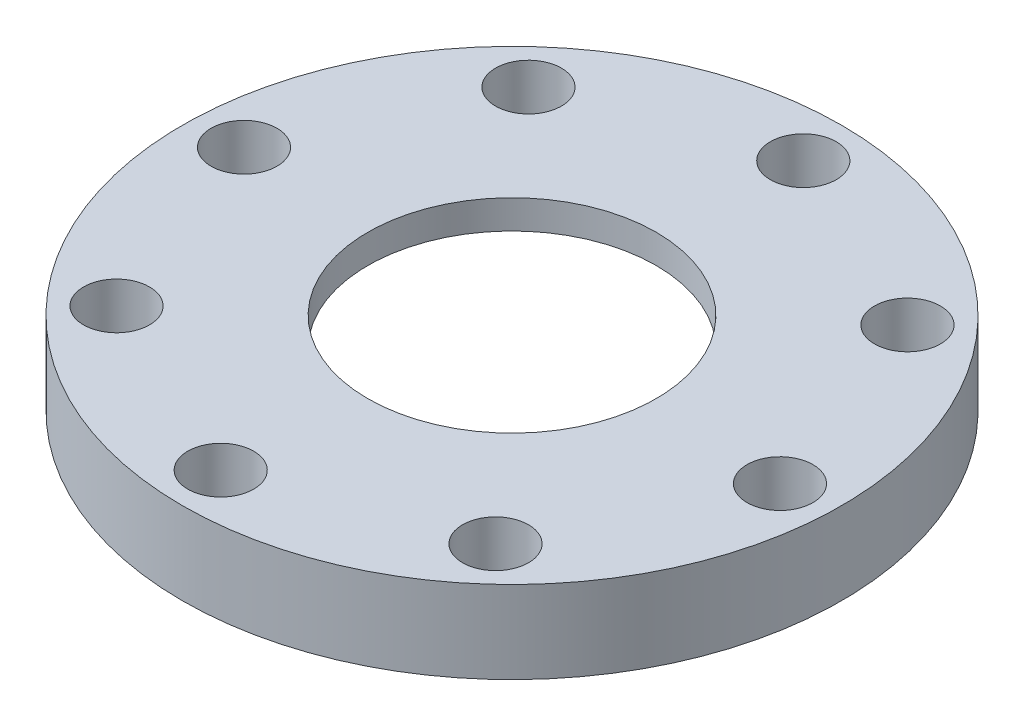
SolidWorks part; units mm, degrees
ref_plane "Front Plane" through (0, 0, 0) normal (0, 0, 1) x (1, 0, 0)
ref_plane "Top Plane" through (0, 0, 0) normal (0, 1, 0) x (1, 0, 0)
ref_plane "Right Plane" through (0, 0, 0) normal (1, 0, 0) x (0, 0, -1)
sketch "Sketch1" plane through (0, 0, 0) normal (0, 1, 0) x (1, 0, 0)
  circle A0 centre (0, 0) radius 40
  dimension "D1" = 80
extrude "Boss-Extrude1" add sketch "Sketch1" along normal blind 10
sketch "Sketch3" plane through (0, 0, 0) normal (0, -1, 0) x (1, 0, 0)
  circle A0 centre (0, 0) radius 27.5
  dimension "D1" = 55
extrude "Cut-Extrude2" cut sketch "Sketch3" against normal blind 6.5
sketch "Sketch4" plane through (0, 10, 0) normal (0, 1, 0) x (1, 0, 0)
  circle A0 centre (0, 0) radius 17.5
  dimension "D1" = 35
extrude "Cut-Extrude3" cut sketch "Sketch4" against normal through all
sketch "Sketch5" plane through (0, 0, 0) normal (0, -1, 0) x (1, 0, 0)
  circle A0 centre (0, 0) radius 33.9706
  circle A1 centre (-25, 23) radius 4
  circle A2 centre (-1.4142, 33.9411) radius 4
  circle A3 centre (23, 25) radius 4
  circle A4 centre (33.9411, 1.4142) radius 4
  circle A5 centre (25, -23) radius 4
  circle A6 centre (1.4142, -33.9411) radius 4
  circle A7 centre (-23, -25) radius 4
  circle A8 centre (-33.9411, -1.4142) radius 4
  point P21 (0, 0)
  dimension "D1" = 23
  dimension "D2" = 8
  dimension "D3" = 25
  dimension "D4" = 8
extrude "Cut-Extrude4" cut sketch "Sketch5" against normal through all contours A2 | A3 | A4 | A5 | A6 | A7 | A8 | A1
cosmetic thread "Cosmetic Thread1" parameters "D2"=10
cosmetic thread "Cosmetic Thread2" parameters "D2"=10
cosmetic thread "Cosmetic Thread3" parameters "D2"=10
cosmetic thread "Cosmetic Thread4" parameters "D2"=10
cosmetic thread "Cosmetic Thread5" parameters "D2"=10
cosmetic thread "Cosmetic Thread6" parameters "D2"=10
cosmetic thread "Cosmetic Thread7" parameters "D2"=10
cosmetic thread "Cosmetic Thread8" parameters "D2"=10
